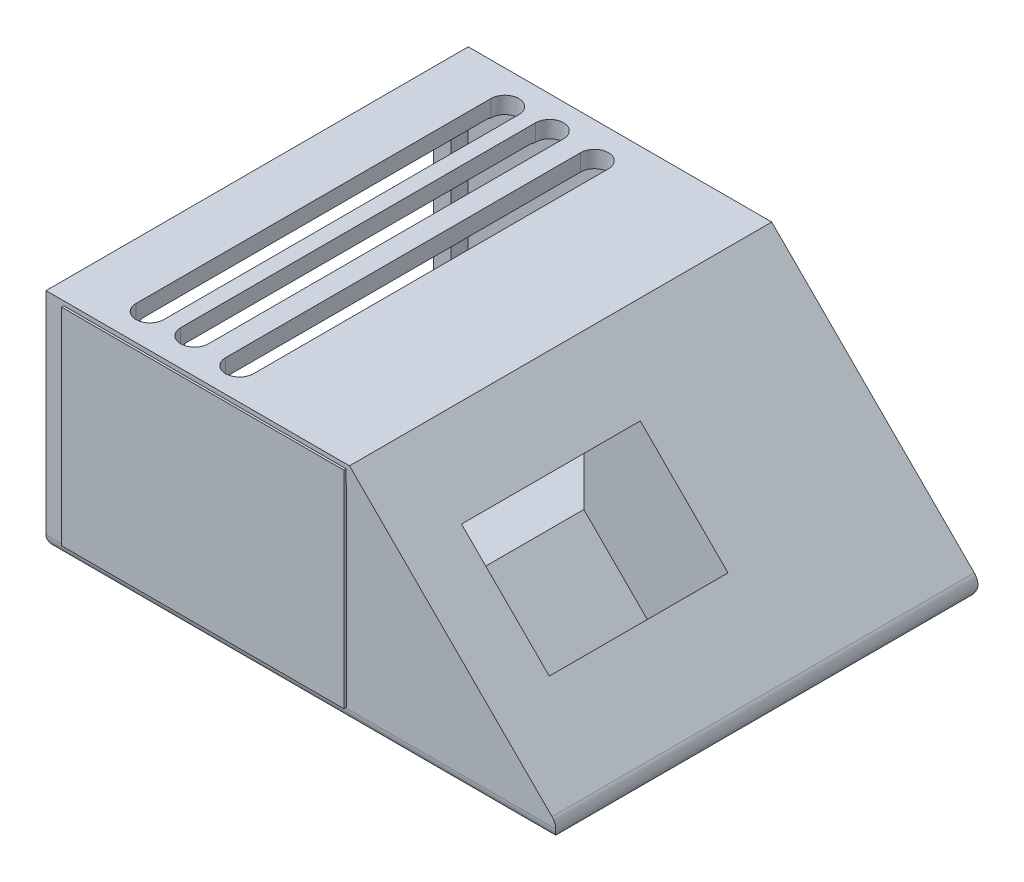
SolidWorks part; units mm, degrees
ref_plane "Ön Düzlem" through (0, 0, 0) normal (0, 0, 1) x (1, 0, 0)
ref_plane "Üst Düzlem" through (0, 0, 0) normal (0, 1, 0) x (1, 0, 0)
ref_plane "Sağ Düzlem" through (0, 0, 0) normal (1, 0, 0) x (0, 0, -1)
sketch "Çizim1" plane through (0, 0, 0) normal (0, 0, 1) x (1, 0, 0)
  line L0 (-100.1173, 48.909) -> (-39.3251, 48.909)
  line L1 (-39.3251, 48.909) -> (5.5811, 4.0028)
  line L2 (5.5811, 4.0028) -> (-100.1173, 4.0028)
  line L3 (-100.1173, 4.0028) -> (-100.1173, 48.909)
extrude "Yükseklik-Ekstrüzyon1" add sketch "Çizim1" along normal blind 84.582
sketch "Çizim2" plane through (0, 0, 84.582) normal (0, 0, 1) x (1, 0, 0)
  line L1 (-96.5818, 45.5477) -> (-39.9686, 45.5477)
  line L2 (-96.5818, 45.5477) -> (-96.5818, 6.6423)
  line L3 (-96.5818, 6.6423) -> (-39.9686, 6.6423)
  line L4 (-39.9686, 45.5477) -> (-39.9686, 6.6423)
extrude "Kes-Ekstrüzyon1" cut sketch "Çizim2" against normal blind 84.582
sketch "Çizim3" plane through (4.792, 4.792, 0) normal (0.7071, 0.7071, 0) x (0.7071, -0.7071, 0)
  line L1 (-47.3106, -72.8068) -> (-22.4506, -72.8068)
  line L2 (-47.3106, -72.8068) -> (-47.3106, -37.003)
  line L3 (-47.3106, -37.003) -> (-22.4506, -37.003)
  line L4 (-22.4506, -72.8068) -> (-22.4506, -37.003)
extrude "Kes-Ekstrüzyon2" cut sketch "Çizim3" against normal blind 22.86
sketch "Çizim4" plane through (0, 6.6423, 0.5214) normal (0, 1, 0) x (1, 0, 0)
  line L1 (-96.5497, -84.4968) -> (-39.9813, -84.4968)
  line L2 (-96.5497, -84.4968) -> (-96.5497, -80.7461)
  line L3 (-96.5497, -80.7461) -> (-39.9813, -80.7461)
  line L4 (-39.9813, -84.4968) -> (-39.9813, -80.7461)
extrude "Yükseklik-Ekstrüzyon3" add sketch "Çizim4" along normal blind 41.402
sketch "Çizim5" plane through (0, 6.6423, 0) normal (0, 1, 0) x (1, 0, 0)
  line L1 (-39.8778, -0.1189) -> (-96.7511, -0.1189)
  line L2 (-39.8778, -0.1189) -> (-39.8778, -3.5603)
  line L3 (-39.8778, -3.5603) -> (-96.7511, -3.5603)
  line L4 (-96.7511, -0.1189) -> (-96.7511, -3.5603)
extrude "Yükseklik-Ekstrüzyon4" add sketch "Çizim5" along normal blind 41.402
sketch "Çizim6" plane through (0, 48.909, 0) normal (0, 1, 0) x (1, 0, 0)
  line L0 (-86.0787, -77.805) -> (-86.0787, -6.7004) construction
  line L1 (-88.8708, -77.805) -> (-88.8708, -6.7004)
  line L2 (-83.2866, -77.805) -> (-83.2866, -6.7004)
  line L3 (-77.4099, -77.524) -> (-77.4099, -6.4194) construction
  line L4 (-80.202, -77.524) -> (-80.202, -6.4194)
  line L5 (-74.6177, -77.524) -> (-74.6177, -6.4194)
  line L6 (-67.7093, -78.2117) -> (-67.7093, -7.1071) construction
  line L7 (-70.5014, -78.2117) -> (-70.5014, -7.1071)
  line L8 (-64.9171, -78.2117) -> (-64.9171, -7.1071)
  arc A0 (-88.8708, -77.805) -> (-83.2866, -77.805) centre (-86.0787, -77.805) ccw
  arc A1 (-83.2866, -6.7004) -> (-88.8708, -6.7004) centre (-86.0787, -6.7004) ccw
  arc A2 (-80.202, -77.524) -> (-74.6177, -77.524) centre (-77.4099, -77.524) ccw
  arc A3 (-74.6177, -6.4194) -> (-80.202, -6.4194) centre (-77.4099, -6.4194) ccw
  arc A4 (-70.5014, -78.2117) -> (-64.9171, -78.2117) centre (-67.7093, -78.2117) ccw
  arc A5 (-64.9171, -7.1071) -> (-70.5014, -7.1071) centre (-67.7093, -7.1071) ccw
  point P2 (-86.0787, -42.2527)
  point P9 (-77.4099, -41.9717)
  point P16 (-67.7093, -42.6594)
extrude "Kes-Ekstrüzyon3" cut sketch "Çizim6" against normal blind 20.828
sketch "Çizim7" plane through (-100.1173, 0, 0) normal (-1, 0, 0) x (0, 0, 1)
  line L1 (7.0052, 45.734) -> (76.7755, 45.734)
  line L2 (7.0052, 45.734) -> (7.0052, 6.7981)
  line L3 (7.0052, 6.7981) -> (76.7755, 6.7981)
  line L4 (76.7755, 45.734) -> (76.7755, 6.7981)
extrude "Kes-Ekstrüzyon4" cut sketch "Çizim7" against normal blind 20.828
fillet "Radyus1" radius 2.54 4 edges at (-100.1173, 4.0028, 42.291) (-47.2681, 4.0028, 84.582) (5.5811, 4.0028, 42.291) (-47.2681, 4.0028, 0)
